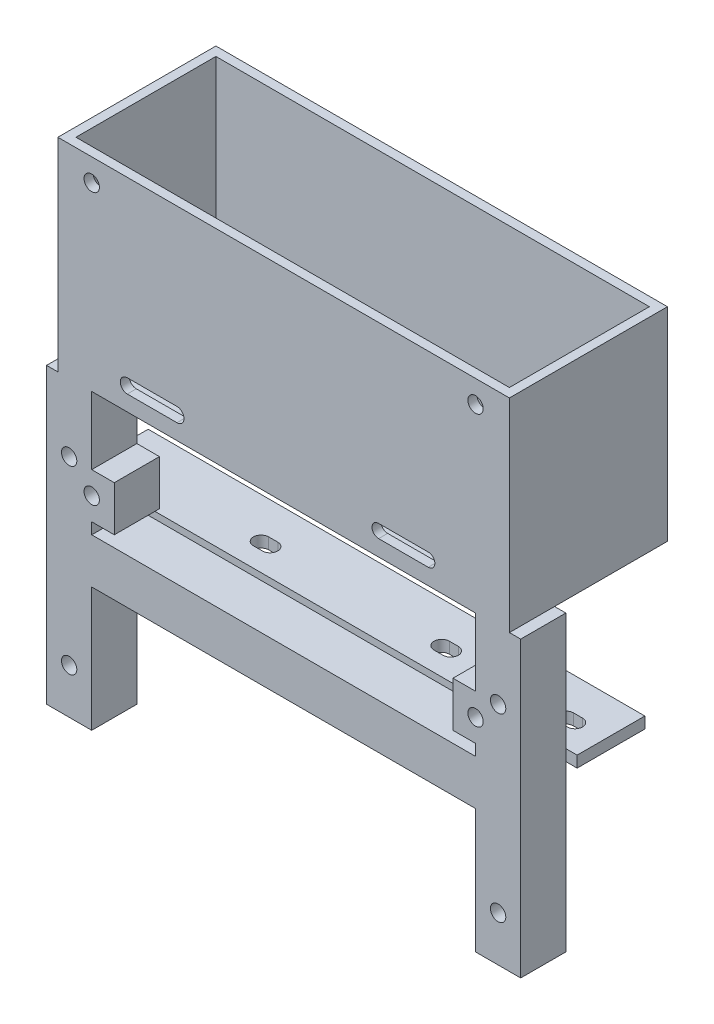
SolidWorks part; units mm, degrees
ref_plane "前视基准面" through (0, 0, 0) normal (0, 0, 1) x (1, 0, 0)
ref_plane "上视基准面" through (0, 0, 0) normal (0, 1, 0) x (1, 0, 0)
ref_plane "右视基准面" through (0, 0, 0) normal (1, 0, 0) x (0, 0, -1)
other "Configuration Table"
sketch "V3 box footprint 100 x 45 mm" plane through (0, 0, 0) normal (0, 0, 1) x (1, 0, 0)
  line L1 (-50, 0) -> (50, 0)
  line L2 (-50, 0) -> (-50, 45)
  line L3 (-50, 45) -> (50, 45)
  line L4 (50, 0) -> (50, 45)
extrude "V3 box height 35 mm" add sketch "V3 box footprint 100 x 45 mm" along normal blind 35
sketch "V3 rear opening 96 x 31 mm" plane through (0, 45, 0) normal (0, 1, 0) x (1, 0, 0)
  line L1 (-48, -2) -> (48, -2)
  line L2 (-48, -2) -> (-48, -33)
  line L3 (-48, -33) -> (48, -33)
  line L4 (48, -2) -> (48, -33)
extrude "V3 cavity all walls 2 mm" cut sketch "V3 rear opening 96 x 31 mm" against normal blind 43
sketch "V3 square beams 10 x 10 pitch 95 mm" plane through (0, 0, 0) normal (0, -1, 0) x (1, 0, 0)
  line L1 (-52.5, 25) -> (-42.5, 25)
  line L2 (-52.5, 25) -> (-52.5, 35)
  line L3 (-52.5, 35) -> (-42.5, 35)
  line L4 (-42.5, 25) -> (-42.5, 35)
  line L6 (42.5, 25) -> (52.5, 25)
  line L7 (42.5, 25) -> (42.5, 35)
  line L8 (42.5, 35) -> (52.5, 35)
  line L9 (52.5, 25) -> (52.5, 35)
extrude "V3 forward beam length 65 mm" add sketch "V3 square beams 10 x 10 pitch 95 mm" along normal blind 65
sketch "V3 left PCB ear profile" plane through (-42.5, 0, 0) normal (1, 0, 0) x (0, 0, -1)
  line L1 (-25, -25) -> (-35, -25)
  line L2 (-25, -25) -> (-25, -15)
  line L3 (-25, -15) -> (-35, -15)
  line L4 (-35, -25) -> (-35, -15)
extrude "V3 left inward ear 5 mm" add sketch "V3 left PCB ear profile" along normal blind 5
sketch "V3 right PCB ear profile" plane through (42.5, 0, 0) normal (-1, 0, 0) x (0, 0, 1)
  line L1 (25, -25) -> (35, -25)
  line L2 (25, -25) -> (25, -15)
  line L3 (25, -15) -> (35, -15)
  line L4 (35, -25) -> (35, -15)
extrude "V3 right inward ear 5 mm" add sketch "V3 right PCB ear profile" along normal blind 5
sketch "V3 PCB roof pair pitch 85 mm" plane through (0, 0, 35) normal (0, 0, 1) x (1, 0, 0)
  circle A0 centre (-42.5, 40) radius 1.7
  circle A1 centre (42.5, 40) radius 1.7
extrude "V3 M3 roof holes diameter 3.4 mm" cut sketch "V3 PCB roof pair pitch 85 mm" against normal blind 2
sketch "V3 PCB forward pair row spacing 60 mm" plane through (0, 0, 35) normal (0, 0, 1) x (1, 0, 0)
  circle A0 centre (-42.5, -20) radius 1.7
  circle A1 centre (42.5, -20) radius 1.7
extrude "V3 M3 PCB ear holes" cut sketch "V3 PCB forward pair row spacing 60 mm" against normal blind 10
sketch "V3 chassis top holes width 95 depth 40 mm" plane through (0, 0, 35) normal (0, 0, 1) x (1, 0, 0)
  circle A0 centre (-47.5, -55) radius 1.7
  circle A1 centre (-47.5, -15) radius 1.7
  circle A2 centre (47.5, -55) radius 1.7
  circle A3 centre (47.5, -15) radius 1.7
extrude "V3 M3 beam top bottom holes" cut sketch "V3 chassis top holes width 95 depth 40 mm" against normal blind 10
sketch "V3 hanging plate offset 26 thickness 2.5 mm" plane through (0, 0, 25) normal (0, 0, -1) x (-1, 0, 0)
  line L1 (55, -28.5) -> (-55, -28.5)
  line L2 (55, -28.5) -> (55, -26)
  line L3 (55, -26) -> (-55, -26)
  line L4 (-55, -28.5) -> (-55, -26)
extrude "V3 mounting plate downward 15 mm width 110" add sketch "V3 hanging plate offset 26 thickness 2.5 mm" along normal blind 15
sketch "V3 slots 6 mm below beam underside centers 20 and 47.5" plane through (0, -28.5, 0) normal (0, -1, 0) x (1, 0, 0)
  line L0 (-48.5, 19) -> (-46.5, 19) construction
  line L1 (-48.5, 20.7) -> (-46.5, 20.7)
  line L2 (-48.5, 17.3) -> (-46.5, 17.3)
  line L3 (-21, 19) -> (-19, 19) construction
  line L4 (-21, 20.7) -> (-19, 20.7)
  line L5 (-21, 17.3) -> (-19, 17.3)
  line L6 (19, 19) -> (21, 19) construction
  line L7 (19, 20.7) -> (21, 20.7)
  line L8 (19, 17.3) -> (21, 17.3)
  line L9 (46.5, 19) -> (48.5, 19) construction
  line L10 (46.5, 20.7) -> (48.5, 20.7)
  line L11 (46.5, 17.3) -> (48.5, 17.3)
  arc A0 (-48.5, 20.7) -> (-48.5, 17.3) centre (-48.5, 19) ccw
  arc A1 (-46.5, 17.3) -> (-46.5, 20.7) centre (-46.5, 19) ccw
  arc A2 (-21, 20.7) -> (-21, 17.3) centre (-21, 19) ccw
  arc A3 (-19, 17.3) -> (-19, 20.7) centre (-19, 19) ccw
  arc A4 (19, 20.7) -> (19, 17.3) centre (19, 19) ccw
  arc A5 (21, 17.3) -> (21, 20.7) centre (21, 19) ccw
  arc A6 (46.5, 20.7) -> (46.5, 17.3) centre (46.5, 19) ccw
  arc A7 (48.5, 17.3) -> (48.5, 20.7) centre (48.5, 19) ccw
  point P2 (-47.5, 19)
  point P7 (-20, 19)
  point P14 (20, 19)
  point P21 (47.5, 19)
  dimension "D1" = 3.4
  dimension "D2" = 2
  dimension "D3" = 3.4
  dimension "D4" = 2
  dimension "D5" = 3.4
  dimension "D6" = 2
  dimension "D7" = 3.4
  dimension "D8" = 2
extrude "Four horizontal slots 3.4 x 5.4 mm" cut sketch "V3 slots 6 mm below beam underside centers 20 and 47.5" against normal blind 2.5
sketch "草图1" plane through (0, 0, 35) normal (0, 0, 1) x (1, 0, 0)
  line L0 (-34.6201, 5) -> (-23.6201, 5) construction
  line L1 (-34.6201, 6.488) -> (-23.6201, 6.488)
  line L2 (-34.6201, 3.512) -> (-23.6201, 3.512)
  line L3 (21.03, 5) -> (32.03, 5) construction
  line L6 (21.03, 6.488) -> (32.03, 6.488)
  line L7 (21.03, 3.512) -> (32.03, 3.512)
  arc A0 (-34.6201, 6.488) -> (-34.6201, 3.512) centre (-34.6201, 5) ccw
  arc A1 (-23.6201, 3.512) -> (-23.6201, 6.488) centre (-23.6201, 5) ccw
  arc A4 (21.03, 6.488) -> (21.03, 3.512) centre (21.03, 5) ccw
  arc A5 (32.03, 3.512) -> (32.03, 6.488) centre (32.03, 5) ccw
  point P2 (-29.1201, 5)
  point P9 (26.53, 5)
sketch "草图2" plane through (0, 0, 0) normal (0, 0, -1) x (-1, 0, 0)
  line L0 (-32.03, 5) -> (-21.03, 5) construction
  line L1 (-32.03, 6.4595) -> (-21.03, 6.4595)
  line L2 (-32.03, 3.5405) -> (-21.03, 3.5405)
  line L3 (23.6201, 5) -> (34.6201, 5) construction
  line L4 (23.6201, 6.5587) -> (34.6201, 6.5587)
  line L5 (23.6201, 3.4413) -> (34.6201, 3.4413)
  arc A0 (-32.03, 6.4595) -> (-32.03, 3.5405) centre (-32.03, 5) ccw
  arc A1 (-21.03, 3.5405) -> (-21.03, 6.4595) centre (-21.03, 5) ccw
  arc A2 (23.6201, 6.5587) -> (23.6201, 3.4413) centre (23.6201, 5) ccw
  arc A3 (34.6201, 3.4413) -> (34.6201, 6.5587) centre (34.6201, 5) ccw
  point P4 (-26.53, 5)
  point P9 (29.1201, 5)
extrude "切除-拉伸1" cut sketch "草图2" against normal through all
sketch "H crossmember 10 x 10 mm at beam midpoint" plane through (-42.5, 0, 0) normal (1, 0, 0) x (0, 0, -1)
  line L1 (-25, -37.5) -> (-35, -37.5)
  line L2 (-25, -37.5) -> (-25, -27.5)
  line L3 (-25, -27.5) -> (-35, -27.5)
  line L4 (-35, -37.5) -> (-35, -27.5)
extrude "H crossmember 85 mm" add sketch "H crossmember 10 x 10 mm at beam midpoint" along normal blind 85
sketch "Beam cavities 6 mm wide preserving screw collars" plane through (0, 0, 35) normal (0, 0, 1) x (1, 0, 0)
  line L1 (-50.5, -65) -> (-44.5, -65)
  line L2 (-50.5, -65) -> (-50.5, -59)
  line L3 (-50.5, -59) -> (-44.5, -59)
  line L4 (-44.5, -65) -> (-44.5, -59)
  line L6 (-50.5, -51) -> (-44.5, -51)
  line L7 (-50.5, -51) -> (-50.5, -24)
  line L8 (-50.5, -24) -> (-44.5, -24)
  line L9 (-44.5, -51) -> (-44.5, -24)
  line L11 (-50.5, -11) -> (-44.5, -11)
  line L12 (-50.5, -11) -> (-50.5, -2)
  line L13 (-50.5, -2) -> (-44.5, -2)
  line L14 (-44.5, -11) -> (-44.5, -2)
  line L16 (44.5, -65) -> (50.5, -65)
  line L17 (44.5, -65) -> (44.5, -59)
  line L18 (44.5, -59) -> (50.5, -59)
  line L19 (50.5, -65) -> (50.5, -59)
  line L21 (44.5, -51) -> (50.5, -51)
  line L22 (44.5, -51) -> (44.5, -24)
  line L23 (44.5, -24) -> (50.5, -24)
  line L24 (50.5, -51) -> (50.5, -24)
  line L26 (44.5, -11) -> (50.5, -11)
  line L27 (44.5, -11) -> (44.5, -2)
  line L28 (44.5, -2) -> (50.5, -2)
  line L29 (50.5, -11) -> (50.5, -2)
extrude "Longitudinal beam walls 2 mm - inner height 6 mm" cut sketch "Beam cavities 6 mm wide preserving screw collars" against normal blind 6 from offset 2
sketch "H crossmember cavity connects both beam cavities" plane through (0, 0, 35) normal (0, 0, 1) x (1, 0, 0)
  line L1 (-44.5, -35.5) -> (44.5, -35.5)
  line L2 (-44.5, -35.5) -> (-44.5, -29.5)
  line L3 (-44.5, -29.5) -> (44.5, -29.5)
  line L4 (44.5, -35.5) -> (44.5, -29.5)
extrude "H crossmember walls 2 mm" cut sketch "H crossmember cavity connects both beam cavities" against normal blind 6 from offset 2
